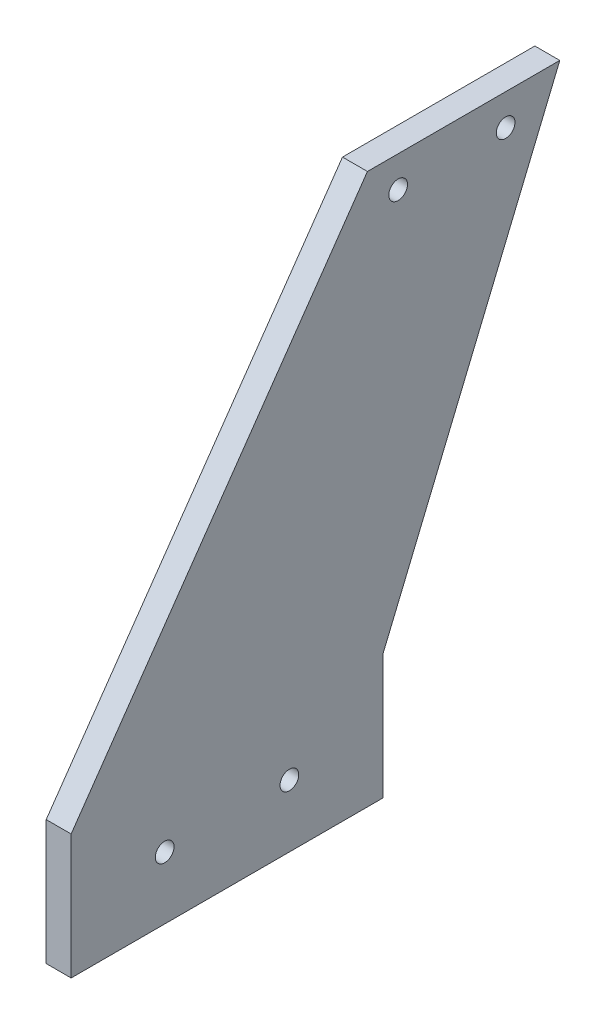
SolidWorks part; units mm, degrees
ref_plane "Alzado" through (0, 0, 0) normal (0, 0, 1) x (1, 0, 0)
ref_plane "Planta" through (0, 0, 0) normal (0, 1, 0) x (1, 0, 0)
ref_plane "Vista lateral" through (0, 0, 0) normal (1, 0, 0) x (0, 0, -1)
sketch "Croquis1" plane through (0, 0, 0) normal (1, 0, 0) x (0, 0, -1)
  line L0 (31.7775, 8.603) -> (79.2917, 76.856)
  line L1 (81.7775, 8.603) -> (81.7775, -11.397)
  line L2 (81.7775, -11.397) -> (31.7775, -11.397)
  line L3 (31.7775, -11.397) -> (31.7775, 8.603)
  line L4 (110.1413, 76.856) -> (79.2917, 76.856)
  line L6 (81.7775, 8.603) -> (110.1413, 76.856)
  dimension "D2" = 50
  dimension "D4" = 20
extrude "Saliente-Extruir1" add sketch "Croquis1" along normal blind 4
sketch "Croquis2" plane through (4, 0, 0) normal (1, 0, 0) x (0, 0, -1)
  circle A0 centre (84.2148, 71.856) radius 1.5
  circle A1 centre (101.4527, 71.856) radius 1.5
extrude "Cortar-Extruir1" cut sketch "Croquis2" against normal blind 13
sketch "Croquis3" plane through (0, 0, 0) normal (-1, 0, 0) x (0, 0, 1)
  line L0 (-81.7775, -1.397) -> (-31.7775, -1.397) construction
  line L1 (-81.7775, -11.397) -> (-81.7775, 8.603) construction
  line L2 (-31.7775, 8.603) -> (-31.7775, -11.397) construction
  circle A0 centre (-66.7775, -1.397) radius 1.5
  circle A1 centre (-46.7775, -1.397) radius 1.5
  dimension "D1" = 3
  dimension "D2" = 3
  dimension "D3" = 15
  dimension "D4" = 15
extrude "Cortar-Extruir2" cut sketch "Croquis3" against normal blind 23
